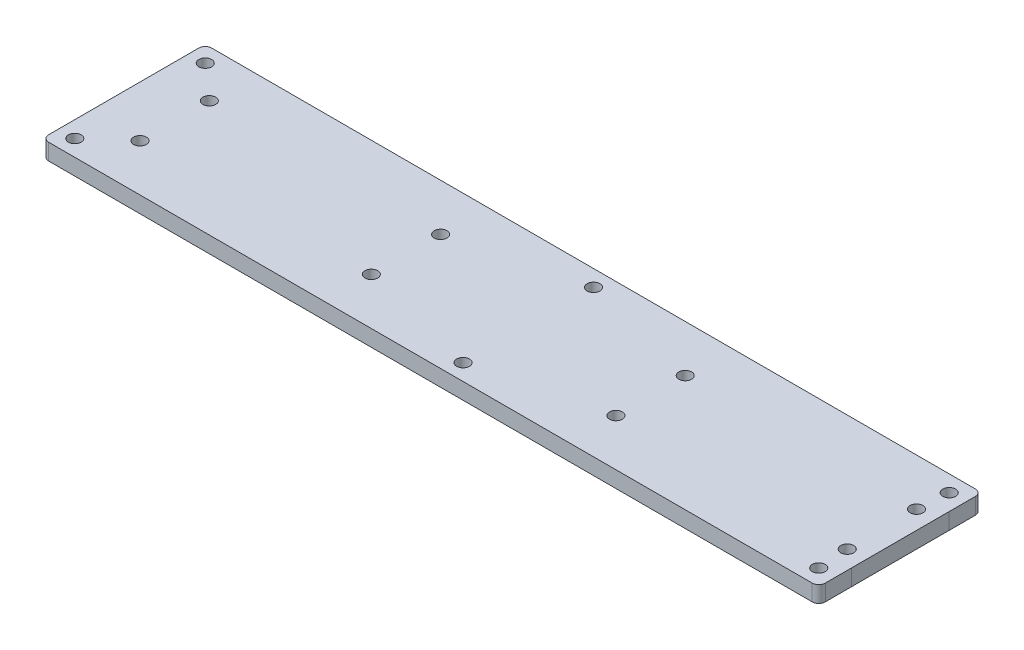
SolidWorks part; units mm, degrees
ref_plane "Front Plane" through (0, 0, 0) normal (0, 0, 1) x (1, 0, 0)
ref_plane "Top Plane" through (0, 0, 0) normal (0, 1, 0) x (1, 0, 0)
ref_plane "Right Plane" through (0, 0, 0) normal (1, 0, 0) x (0, 0, -1)
sketch "Sketch1" plane through (0, 0, 0) normal (0, 1, 0) x (1, 0, 0)
  line L1 (-144.845, 19.05) -> (144.845, 19.05)
  line L2 (-144.845, 19.05) -> (-144.845, -19.05)
  line L3 (-144.845, -19.05) -> (144.845, -19.05)
  line L4 (144.845, 19.05) -> (144.845, -19.05)
  line L5 (-144.845, 19.05) -> (144.845, -19.05) construction
  line L6 (-144.845, -19.05) -> (144.845, 19.05) construction
  line L7 (144.845, -19.05) -> (144.845, -31.75)
  line L8 (-144.845, 19.05) -> (144.845, 19.05)
  line L9 (-144.845, 19.05) -> (-144.845, 31.75)
  line L10 (-144.845, 31.75) -> (144.845, 31.75)
  line L11 (144.845, 19.05) -> (144.845, 31.75)
  line L12 (-144.845, -19.05) -> (144.845, -19.05)
  line L13 (-144.845, -19.05) -> (-144.845, -31.75)
  line L14 (-144.845, -31.75) -> (144.845, -31.75)
  line L15 (144.845, -19.05) -> (144.845, -31.75)
  line L16 (-144.845, 31.75) -> (-157.545, 31.75)
  line L17 (-144.845, 31.75) -> (-144.845, -31.75)
  line L18 (-144.845, -31.75) -> (-157.545, -31.75)
  line L19 (-157.545, 31.75) -> (-157.545, -31.75)
  line L20 (144.845, 31.75) -> (144.845, 19.05)
  circle A0 centre (-151.195, 25.4) radius 2.49
  circle A2 centre (-151.195, -25.4) radius 2.49
  circle A3 centre (0, 25.4) radius 2.49
  circle A4 centre (0, -25.4) radius 2.49
  circle A5 centre (138.495, 25.4) radius 2.49
  circle A6 centre (138.495, -25.4) radius 2.49
  point P0 (0, 0)
  dimension "D7" = 6.35
  dimension "D8" = 6.35
  dimension "D9" = 4.98
  dimension "D10" = 4.98
  dimension "D11" = 4.98
  dimension "D12" = 6.35
  dimension "D13" = 4.98
  dimension "D14" = 4.98
  dimension "D15" = 4.98
  dimension "D16" = 6.35
  dimension "D18" = 6.35
  dimension "D19" = 144.845
  dimension "D21" = 144.845
  dimension "D24" = 6.35
  dimension "D3" = 6.35
  dimension "D1" = 289.69
  dimension "D2" = 38.1
  dimension "D4" = 12.7
  dimension "D5" = 12.7
  dimension "D6" = 12.7
  dimension "D17" = 6.35
  dimension "D20" = 6.35
  dimension "D22" = 6.35
  dimension "D23" = 289.69
  dimension "D25" = 6.35
extrude "Boss-Extrude1" add sketch "Sketch1" along normal blind 6.35 contours L13 L14 L7 L3 A6 A4 | L16 L19 L18 L13 L2 L9 A2 A0 | L1 L11 L10 L9 A5 A3
fillet "Fillet1" radius 2.54 4 edges at (144.845, 3.175, -31.75) (-157.545, 3.175, -31.75) (-157.545, 3.175, 31.75) (144.845, 3.175, 31.75)
sketch "Sketch3" plane through (0, 6.35, 0) normal (0, 1, 0) x (1, 0, 0)
  line L1 (-144.845, -19.05) -> (144.842, -19.05)
  line L2 (-144.845, -19.05) -> (-144.845, 19.05)
  line L3 (-144.845, 19.05) -> (144.842, 19.05)
  line L4 (144.842, -19.05) -> (144.842, 19.05)
  circle A0 centre (-137.7076, 13.4874) radius 2.4892
  circle A1 centre (-137.733, -13.4874) radius 2.4892
  circle A2 centre (-47.6392, -13.4874) radius 2.4892
  circle A3 centre (-47.6392, 13.4874) radius 2.4892
  circle A4 centre (47.6108, 13.4874) radius 2.4892
  circle A5 centre (47.6108, -13.4874) radius 2.4892
  circle A6 centre (137.6792, 13.4874) radius 2.4892
  circle A7 centre (137.6792, -13.4874) radius 2.4892
  point P21 (0, 0)
  point P22 (0, 0)
  point P23 (0, 0)
  point P24 (0, 0)
  point P25 (0, 0)
  dimension "D3" = 4.9784
  dimension "D4" = 5.5626
  dimension "D5" = 7.1374
  dimension "D6" = 5.5626
  dimension "D7" = 7.112
  dimension "D8" = 90.0684
  dimension "D9" = 95.25
  dimension "D10" = 90.0684
  dimension "D1" = 38.1
  dimension "D2" = 289.687
extrude "Boss-Extrude2" add sketch "Sketch3" against normal up to surface (6.35 mm away) up to face at (138.495, 0, 27.89)
